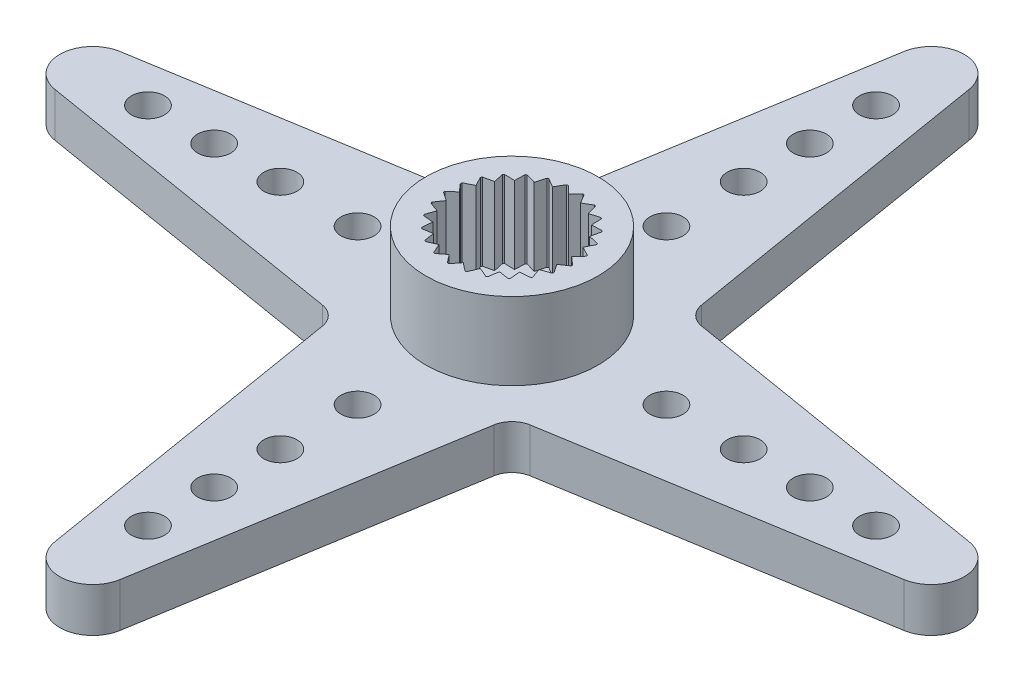
SolidWorks part; units mm, degrees
ref_plane "Front Plane" through (0, 0, 0) normal (0, 0, 1) x (1, 0, 0)
ref_plane "Top Plane" through (0, 0, 0) normal (0, 1, 0) x (1, 0, 0)
ref_plane "Right Plane" through (0, 0, 0) normal (1, 0, 0) x (0, 0, -1)
sketch "Sketch1" plane through (0, 0, 0) normal (0, 1, 0) x (1, 0, 0)
  line L0 (-15.5, 0) -> (15.5, 0) construction
  line L1 (4, -4) -> (-4, -4) construction
  line L2 (0, 19) -> (0, -19) construction
  line L7 (4, -4) -> (4, 4) construction
  line L8 (4, 4) -> (-4, 4) construction
  line L9 (-4, 4) -> (-1.4799, 19.2446)
  line L10 (4, 4) -> (1.4799, 19.2446)
  line L11 (4, -4) -> (19.2446, -1.4799)
  line L12 (4, 4) -> (19.2446, 1.4799)
  line L13 (-4, -4) -> (-1.4799, -19.2446)
  line L14 (4, -4) -> (1.4799, -19.2446)
  line L15 (-4, 4) -> (-19.2446, 1.4799)
  line L16 (-4, -4) -> (-4, 4) construction
  line L17 (4, -4) -> (-4, 4) construction
  line L18 (4, 4) -> (-4, -4) construction
  line L19 (-4, -4) -> (-19.2446, -1.4799)
  arc A1 (1.4799, 19.2446) -> (-1.4799, 19.2446) centre (0, 19) ccw
  arc A4 (19.2446, -1.4799) -> (19.2446, 1.4799) centre (19, 0) ccw
  arc A6 (-1.4799, -19.2446) -> (1.4799, -19.2446) centre (0, -19) ccw
  arc A8 (-19.2446, 1.4799) -> (-19.2446, -1.4799) centre (-19, 0) ccw
  point P0 (0, 0)
  point P10 (0, 0)
  point P20 (0, 0)
  point P31 (0, 0)
  dimension "D3" = 4
  dimension "D4" = 4
  dimension "D5" = 3
  dimension "D1" = 38
  dimension "D2" = 8
extrude "Boss-Extrude1" add sketch "Sketch1" along normal blind 2
sketch "Sketch6" plane through (0, 2, 0) normal (0, 1, 0) x (1, 0, 0)
  circle A0 centre (0, 0) radius 3.9
  dimension "D1" = 7.8
extrude "Boss-Extrude3" add sketch "Sketch6" along normal blind 3.5
sketch "Sketch7" plane through (0, 5.5, 0) normal (0, 1, 0) x (1, 0, 0)
  line L0 (-0.331, 2.881) -> (0, 2.55)
  line L1 (0, 2.55) -> (0.331, 2.881)
  line L2 (0.6342, 2.4699) -> (1.0371, 2.7082)
  line L3 (0.3958, 2.8729) -> (0.6342, 2.4699)
  line L4 (1.2285, 2.2346) -> (1.678, 2.3652)
  line L5 (1.0979, 2.6842) -> (1.2285, 2.2346)
  line L6 (1.7456, 1.8589) -> (2.2135, 1.8736)
  line L7 (1.7309, 2.3268) -> (1.7456, 1.8589)
  line L8 (2.153, 1.3664) -> (2.6099, 1.2642)
  line L9 (2.2552, 1.8232) -> (2.153, 1.3664)
  line L10 (2.4252, 0.788) -> (2.8423, 0.5755)
  line L11 (2.6377, 1.2051) -> (2.4252, 0.788)
  line L12 (2.545, 0.1601) -> (2.8961, -0.1495)
  line L13 (2.8546, 0.5113) -> (2.545, 0.1601)
  line L14 (2.5048, -0.4778) -> (2.768, -0.865)
  line L15 (2.892, -0.2147) -> (2.5048, -0.4778)
  line L16 (2.3073, -1.0857) -> (2.4659, -1.5262)
  line L17 (2.7478, -0.9272) -> (2.3073, -1.0857)
  line L18 (1.9648, -1.6254) -> (2.0089, -2.0915)
  line L19 (2.4309, -1.5814) -> (1.9648, -1.6254)
  line L20 (1.4989, -2.063) -> (1.4256, -2.5254)
  line L21 (1.9613, -2.1362) -> (1.4989, -2.063)
  line L22 (0.9387, -2.3709) -> (0.7528, -2.8006)
  line L23 (1.3684, -2.5569) -> (0.9387, -2.3709)
  line L24 (0.3196, -2.5299) -> (0.0327, -2.8998)
  line L25 (0.6895, -2.8168) -> (0.3196, -2.5299)
  line L26 (-0.3196, -2.5299) -> (-0.6895, -2.8168)
  line L27 (-0.0327, -2.8998) -> (-0.3196, -2.5299)
  line L28 (-0.9387, -2.3709) -> (-1.3684, -2.5569)
  line L29 (-0.7528, -2.8006) -> (-0.9387, -2.3709)
  line L30 (-1.4989, -2.063) -> (-1.9613, -2.1362)
  line L31 (-1.4256, -2.5254) -> (-1.4989, -2.063)
  line L32 (-1.9648, -1.6254) -> (-2.4309, -1.5814)
  line L33 (-2.0089, -2.0915) -> (-1.9648, -1.6254)
  line L34 (-2.3073, -1.0857) -> (-2.7478, -0.9272)
  line L35 (-2.4659, -1.5262) -> (-2.3073, -1.0857)
  line L36 (-2.5048, -0.4778) -> (-2.892, -0.2147)
  line L37 (-2.768, -0.865) -> (-2.5048, -0.4778)
  line L38 (-2.545, 0.1601) -> (-2.8546, 0.5113)
  line L39 (-2.8961, -0.1495) -> (-2.545, 0.1601)
  line L40 (-2.4252, 0.788) -> (-2.6377, 1.2051)
  line L41 (-2.8423, 0.5755) -> (-2.4252, 0.788)
  line L42 (-2.153, 1.3664) -> (-2.2552, 1.8232)
  line L43 (-2.6099, 1.2642) -> (-2.153, 1.3664)
  line L44 (-1.7456, 1.8589) -> (-1.7309, 2.3268)
  line L45 (-2.2135, 1.8736) -> (-1.7456, 1.8589)
  line L46 (-1.2285, 2.2346) -> (-1.0979, 2.6842)
  line L47 (-1.678, 2.3652) -> (-1.2285, 2.2346)
  line L48 (-0.6342, 2.4699) -> (-0.3958, 2.8729)
  line L49 (-1.0371, 2.7082) -> (-0.6342, 2.4699)
  circle A0 centre (0, 0) radius 2.9
  circle A1 centre (0, 0) radius 2.55 construction
  point P81 (0, 0)
  dimension "D1" = 5.8
  dimension "D2" = 5.1
  dimension "D3" = 90
  dimension "D4" = 25
extrude "Cut-Extrude3" cut sketch "Sketch7" against normal blind 3.5 contours L25 A0 L22 L23 L20 L21 L18 L19 L16 L17 L14 L15 L12 L13 L10 L11 L8 L9 L6 L7 L4 L5 L2 L3 L1 L0 L48 L49 L46 L47 L44 L45 L42 L43 L40
fillet "Fillet2" radius 1 4 edges at (4, 1, 4) (-4, 1, 4) (-4, 1, -4) (4, 1, -4)
sketch "Sketch8" plane through (0, 2, 0) normal (0, 1, 0) x (1, 0, 0)
  line L0 (0, 20.5) -> (0, 0) construction
  arc A0 (1.4799, 19.2446) -> (-1.4799, 19.2446) centre (0, 19) ccw construction
  circle A1 centre (0, 16.5) radius 0.75
  circle A2 centre (0, 13.5) radius 0.75
  circle A3 centre (0, 10.5) radius 0.75
  circle A4 centre (0, 7) radius 0.75
  circle A5 centre (16.5, 0) radius 0.75
  circle A6 centre (13.5, 0) radius 0.75
  circle A7 centre (10.5, 0) radius 0.75
  circle A8 centre (7, 0) radius 0.75
  circle A9 centre (0, -16.5) radius 0.75
  circle A10 centre (0, -13.5) radius 0.75
  circle A11 centre (0, -10.5) radius 0.75
  circle A12 centre (0, -7) radius 0.75
  circle A13 centre (-16.5, 0) radius 0.75
  circle A14 centre (-13.5, 0) radius 0.75
  circle A15 centre (-10.5, 0) radius 0.75
  circle A16 centre (-7, 0) radius 0.75
  point P41 (0, 0)
  dimension "D2" = 10.5
  dimension "D3" = 13.5
  dimension "D5" = 1.5
  dimension "D1" = 7
  dimension "D4" = 16.5
  dimension "D6" = 4
extrude "Cut-Extrude4" cut sketch "Sketch8" against normal through all
sketch "Sketch9" plane through (0, 2, 0) normal (0, 1, 0) x (1, 0, 0)
  circle A0 centre (0, 0) radius 1.5
  dimension "D1" = 3
extrude "Cut-Extrude5" cut sketch "Sketch9" against normal through all
